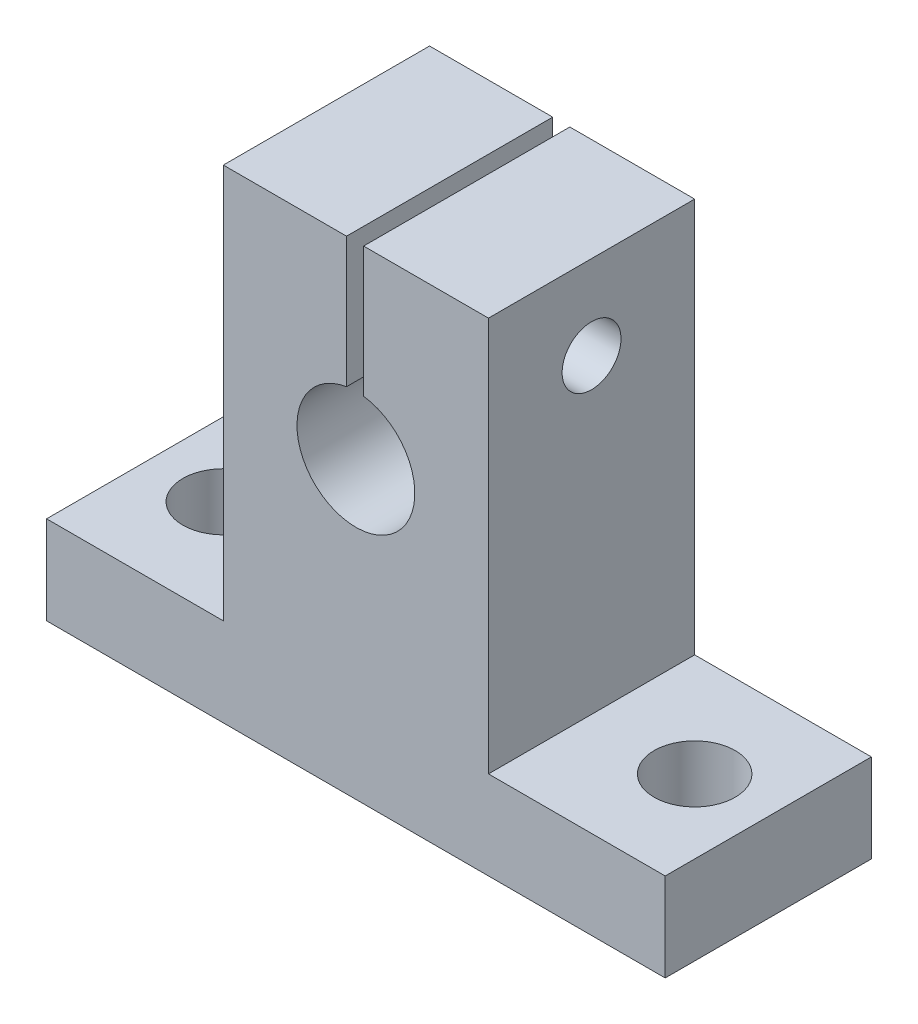
SolidWorks part; units mm, degrees
ref_plane "前视基准面" through (0, 0, 0) normal (0, 0, 1) x (1, 0, 0)
ref_plane "上视基准面" through (0, 0, 0) normal (0, 1, 0) x (1, 0, 0)
ref_plane "右视基准面" through (0, 0, 0) normal (1, 0, 0) x (0, 0, -1)
sketch "草图1" plane through (0, 0, 0) normal (0, 1, 0) x (1, 0, 0)
  line L1 (-14.3576, 5.8998) -> (27.6424, 5.8998)
  line L2 (-14.3576, 5.8998) -> (-14.3576, -8.1002)
  line L3 (-14.3576, -8.1002) -> (27.6424, -8.1002)
  line L4 (27.6424, 5.8998) -> (27.6424, -8.1002)
  line L5 (-14.3576, 5.8998) -> (27.6424, -8.1002) construction
  line L6 (-14.3576, -8.1002) -> (27.6424, 5.8998) construction
  point P4 (6.6424, -1.1002)
  dimension "D1" = 42
  dimension "D2" = 14
extrude "凸台-拉伸1" add sketch "草图1" along normal blind 6
sketch "草图2" plane through (0, 6, 0) normal (0, 1, 0) x (1, 0, 0)
  line L0 (27.6424, -8.1002) -> (27.6424, 5.8998) construction
  circle A0 centre (-9.3576, -1.1002) radius 2.75
  circle A1 centre (22.6424, -1.1002) radius 2.75
  dimension "D2" = 5.5
  dimension "D3" = 5.5
  dimension "D4" = 5
  dimension "D1" = 32
extrude "切除-拉伸1" cut sketch "草图2" against normal through all
sketch "草图3" plane through (0, 6, 0) normal (0, 1, 0) x (1, 0, 0)
  line L0 (6.6424, 5.8998) -> (6.6424, -8.1002) construction
  line L1 (27.6424, 5.8998) -> (-14.3576, 5.8998) construction
  line L2 (-14.3576, -8.1002) -> (27.6424, -8.1002) construction
  line L4 (-2.3576, 5.8998) -> (15.6424, 5.8998)
  line L5 (-2.3576, 5.8998) -> (-2.3576, -8.1002)
  line L6 (-2.3576, -8.1002) -> (15.6424, -8.1002)
  line L7 (15.6424, 5.8998) -> (15.6424, -8.1002)
  line L8 (-2.3576, 5.8998) -> (15.6424, -8.1002) construction
  line L9 (-2.3576, -8.1002) -> (15.6424, 5.8998) construction
  point P10 (6.6424, -1.1002)
  point P11 (7.2177, -1.1002)
  point P12 (6.6424, -1.1002)
  dimension "D1" = 18
extrude "凸台-拉伸2" add sketch "草图3" along normal blind 26.8
sketch "草图4" plane through (0, 0, 8.1002) normal (0, 0, 1) x (1, 0, 0)
  line L0 (-14.3576, 0) -> (27.6424, 0) construction
  circle A0 centre (6.6424, 20) radius 4
  dimension "D1" = 8
  dimension "D2" = 20
extrude "切除-拉伸2" cut sketch "草图4" against normal through all
sketch "草图5" plane through (0, 0, -5.8998) normal (0, 0, -1) x (-1, 0, 0)
  line L0 (-15.6424, 32.8) -> (2.3576, 32.8) construction
  line L1 (-7.1669, 32.8) -> (-6.0057, 32.8)
  line L2 (-7.1669, 32.8) -> (-7.1669, 23.949)
  line L3 (-7.1669, 23.949) -> (-6.0057, 23.949)
  line L4 (-6.0057, 32.8) -> (-6.0057, 23.949)
  line L5 (-7.1669, 32.8) -> (-6.0057, 23.949) construction
  line L6 (-7.1669, 23.949) -> (-6.0057, 32.8) construction
  circle A0 centre (-6.6424, 20) radius 4 construction
  point P4 (-6.5863, 28.3745)
  point P9 (-6.2933, 23.9847)
extrude "切除-拉伸3" cut sketch "草图5" against normal through all
sketch "草图7" plane through (-2.3576, 0, 0) normal (-1, 0, 0) x (0, 0, 1)
  circle A0 centre (1.1002, 27.0916) radius 2
  dimension "D1" = 4
extrude "切除-拉伸4" cut sketch "草图7" against normal through all
